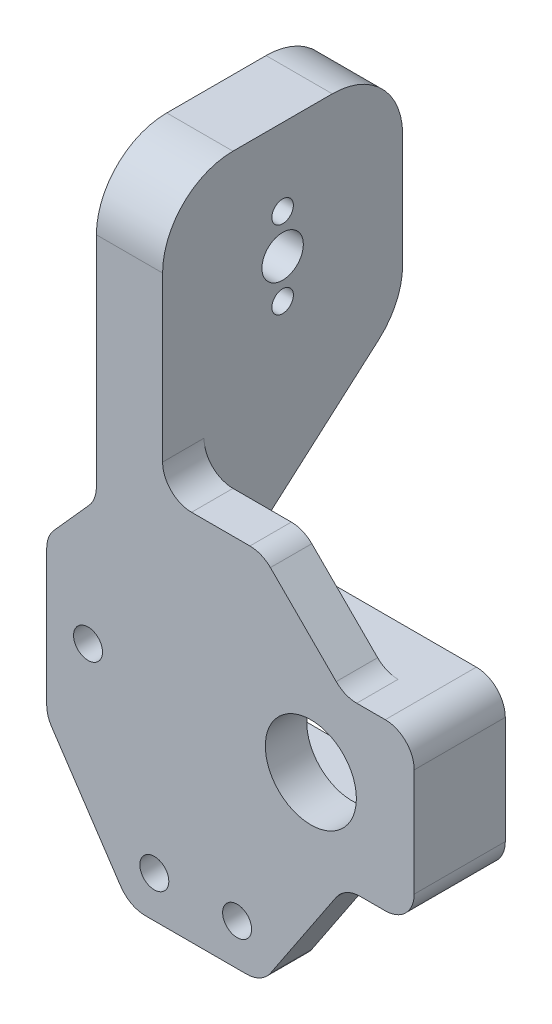
SolidWorks part; units mm, degrees
ref_plane "Front Plane" through (0, 0, 0) normal (0, 0, 1) x (1, 0, 0)
ref_plane "Top Plane" through (0, 0, 0) normal (0, 1, 0) x (1, 0, 0)
ref_plane "Right Plane" through (0, 0, 0) normal (1, 0, 0) x (0, 0, -1)
sketch "Sketch2" plane through (0, 0, 0) normal (0, 0, 1) x (1, 0, 0)
  line L0 (6, -0.2185) -> (14, -0.2185)
  line L1 (14, -0.2185) -> (14, -28)
  line L2 (6, -0.2185) -> (6, -34.9443)
  line L3 (4.9814, -37.6109) -> (1.0186, -42.0415)
  line L4 (0, -44.7082) -> (0, -60.7889)
  line L5 (0.6718, -63.0077) -> (8.8145, -75.2217)
  line L7 (12.1407, -77) -> (23.8593, -77)
  line L8 (34.8125, -63.7812) -> (27.1875, -75.2188)
  line L9 (38.1407, -62) -> (40.4, -62)
  line L10 (44.4, -46) -> (44.4, -58)
  line L11 (37.6569, -42) -> (40.4, -42)
  line L12 (34.8284, -40.8284) -> (27.1716, -33.1716)
  line L13 (18, -32) -> (24.3431, -32)
  line L14 (6, -34.9443) -> (6, -35.1352)
  line L15 (4.9814, -37.6109) -> (5.1087, -37.4685)
  line L16 (0, -60.7889) -> (0, -60.9403)
  line L17 (0.6718, -63.0077) -> (0.5878, -62.8817)
  line L18 (8.8145, -75.2217) -> (9.0744, -75.5748)
  line L19 (12.1407, -77) -> (11.8931, -77)
  line L20 (27.1875, -75.2188) -> (27.0391, -75.4414)
  line L21 (23.8593, -77) -> (24.1269, -77)
  line L22 (34.8125, -63.7812) -> (34.9609, -63.5586)
  line L23 (38.1407, -62) -> (37.8731, -62)
  line L24 (44.4, -58) -> (44.4, -58.5)
  line L25 (40.4, -62) -> (40.9, -62)
  line L26 (40.4, -42) -> (40.9, -42)
  line L27 (44.4, -46) -> (44.4, -45.5)
  line L28 (37.6569, -42) -> (37.4497, -42)
  line L29 (34.8284, -40.8284) -> (34.9749, -40.9749)
  line L30 (14, -28) -> (14, -28.5)
  line L31 (18, -32) -> (17.5, -32)
  line L32 (24.3431, -32) -> (24.5503, -32)
  line L33 (27.1716, -33.1716) -> (27.0251, -33.0251)
  line L34 (1.0186, -42.0415) -> (0.8913, -42.1839)
  line L35 (0, -44.7082) -> (0, -44.5172)
  arc A0 (5.1087, -37.4685) -> (6, -35.1352) centre (2.5, -35.1352) ccw
  arc A1 (0.5878, -62.8817) -> (0, -60.9403) centre (3.5, -60.9403) cw
  arc A2 (11.8931, -77) -> (9.0744, -75.5748) centre (11.8931, -73.5) cw
  arc A3 (24.1269, -77) -> (27.0391, -75.4414) centre (24.1269, -73.5) ccw
  arc A4 (34.9609, -63.5586) -> (37.8731, -62) centre (37.8731, -65.5) cw
  arc A5 (40.9, -62) -> (44.4, -58.5) centre (40.9, -58.5) ccw
  arc A6 (44.4, -45.5) -> (40.9, -42) centre (40.9, -45.5) ccw
  arc A7 (37.4497, -42) -> (34.9749, -40.9749) centre (37.4497, -38.5) cw
  arc A8 (17.5, -32) -> (14, -28.5) centre (17.5, -28.5) cw
  circle A9 centre (31.9101, -52.0014) radius 5.5
  circle A10 centre (23, -72) radius 1.75
  circle A11 centre (13, -72) radius 1.75
  circle A12 centre (4.9951, -52.0029) radius 1.749
  arc A13 (0, -44.5172) -> (0.8913, -42.1839) centre (3.5, -44.5172) cw
  arc A14 (27.0251, -33.0251) -> (24.5503, -32) centre (24.5503, -35.5) ccw
  point P2 (39.2703, -62)
  dimension "D1" = 3.5
  dimension "D3" = 3.5
  dimension "D4" = 3.5
  dimension "D7" = 3.5
  dimension "D8" = 3.5
  dimension "D9" = 3.5
  dimension "D10" = 3.5
  dimension "D11" = 3.5
  dimension "D12" = 3.5
  dimension "D13" = 3.5
  dimension "D25" = 11
  dimension "D26" = 26.915
  dimension "D2" = 180
  dimension "D5" = 14.6794
  dimension "D6" = 3.5553
  dimension "D14" = 76.7815
  dimension "D15" = 44.4
  dimension "D16" = 8
  dimension "D17" = 11.7186
  dimension "D18" = 6
  dimension "D19" = 31.7815
  dimension "D20" = 35
  dimension "D21" = 20
  dimension "D22" = 10.8283
  dimension "D23" = 13.7462
  dimension "D24" = 5.9443
extrude "Boss-Extrude1" add sketch "Sketch2" along normal blind 5
sketch "Sketch3" plane through (0, 0, 0) normal (0, 0, -1) x (-1, 0, 0)
  line L0 (-40.9, -42) -> (-37.4497, -42) construction
  line L1 (-44.4, -58.5) -> (-44.4, -45.5) construction
  line L2 (-37.8731, -62) -> (-40.9, -62) construction
  line L3 (-37.8731, -62) -> (-40.9, -62)
  line L4 (-44.4, -58.5) -> (-44.4, -45.5)
  line L5 (-40.9, -42) -> (-37.4497, -42)
  line L6 (-37.4497, -42) -> (-17.5, -42)
  line L7 (-9.4, -44) -> (-9.4, -58.5)
  line L8 (-12.9, -62) -> (-37.8731, -62)
  line L9 (-14, -0.2185) -> (-6, -0.2185)
  line L10 (-6, -0.2185) -> (-6, -42)
  line L11 (-6, -42) -> (-7.4, -42)
  line L12 (-14, -0.2185) -> (-14, -38.5)
  line L13 (-38.4, -52) -> (-40.7, -52) construction
  line L14 (-38.4, -46) -> (-15.4, -46)
  line L15 (-38.4, -46) -> (-38.4, -58)
  line L16 (-38.4, -58) -> (-15.4, -58)
  line L17 (-15.4, -46) -> (-15.4, -58)
  line L18 (-26.9, -46) -> (-26.9, -58) construction
  line L19 (-15.4, -52) -> (-13.1, -52) construction
  arc A0 (-40.9, -42) -> (-44.4, -45.5) centre (-40.9, -45.5) ccw construction
  arc A1 (-44.4, -58.5) -> (-40.9, -62) centre (-40.9, -58.5) ccw construction
  arc A2 (-44.4, -58.5) -> (-40.9, -62) centre (-40.9, -58.5) ccw
  arc A3 (-40.9, -42) -> (-44.4, -45.5) centre (-40.9, -45.5) ccw
  arc A4 (-14, -38.5) -> (-17.5, -42) centre (-17.5, -38.5) cw
  arc A5 (-9.4, -58.5) -> (-12.9, -62) centre (-12.9, -58.5) cw
  arc A6 (-7.4, -42) -> (-9.4, -44) centre (-7.4, -44) ccw
  circle A7 centre (-40.7, -52) radius 1
  circle A8 centre (-13.1, -52) radius 1
  point P27 (-9.4, -42)
  dimension "D7" = 3.5
  dimension "D8" = 2
  dimension "D9" = 2
  dimension "D1" = 35
  dimension "D2" = 4
  dimension "D3" = 4
  dimension "D4" = 6
  dimension "D5" = 6
  dimension "D6" = 20
  dimension "D10" = 27.6
extrude "Boss-Extrude2" add sketch "Sketch3" along normal blind 6
sketch "Sketch4" plane through (0, 0, -6) normal (0, 0, -1) x (-1, 0, 0)
  line L0 (-14, -0.2185) -> (-6, -0.2185)
  line L1 (-6, -0.2185) -> (-6, -26.2185)
  line L2 (-6, -42) -> (-6, -0.2185) construction
  line L3 (-6, -26.2185) -> (-14, -26.2185)
  line L4 (-14, -0.2185) -> (-14, -38.5) construction
  line L5 (-14, -26.2185) -> (-14, -0.2185)
  dimension "D1" = 26
extrude "Boss-Extrude3" add sketch "Sketch4" along normal blind 18
ref_plane "Plane1" through (10, 0, 0) normal (-1, 0, 0) x (0, 0, 1)
sketch "Sketch5" plane through (10, 0, 0) normal (-1, 0, 0) x (0, 0, 1)
  line L0 (-24, -26.2185) -> (-6, -42)
  line L9 (5, -0.2185) -> (-24, -0.2185)
  line L10 (-24, -0.2185) -> (-24, -26.2185)
  line L11 (-24, -26.2185) -> (-6, -26.2185)
  line L12 (-6, -26.2185) -> (-6, -42)
  line L13 (-6, -42) -> (0, -42)
  line L14 (0, -42) -> (0, -35.1352)
  line L15 (0, -35.1352) -> (5, -35.1352)
  line L16 (5, -35.1352) -> (5, -0.2185)
  line L19 (-24, -26.2185) -> (-6, -26.2185)
  line L20 (-6, -26.2185) -> (-6, -42)
  dimension "D1" = 0
extrude "Boss-Extrude4" add sketch "Sketch5" along normal mid plane 8
fillet "Fillet1" radius 8.5 3 edges at (10, -0.2185, 5) (10, -26.2185, -24) (10, -0.2185, -24)
sketch "Sketch6" plane through (14, 0, 0) normal (1, 0, 0) x (0, 0, -1)
  line L0 (-5, -8.7185) -> (-5, -28.5) construction
  line L1 (3.5, -0.2185) -> (15.5, -0.2185) construction
  line L2 (3.5, -14.2185) -> (15.5, -14.2185) construction
  line L3 (24, -8.7185) -> (24, -22.3666) construction
  line L4 (9.5, -8.7185) -> (9.5, -28.5) construction
  arc A0 (3.5, -0.2185) -> (-5, -8.7185) centre (3.5, -8.7185) ccw construction
  circle A1 centre (9.5, -14.2185) radius 2.5
  circle A2 centre (9.5, -9.5185) radius 1.3
  circle A3 centre (9.5, -18.9185) radius 1.3
  dimension "D6" = 5
  dimension "D7" = 2.6
  dimension "D1" = 29
  dimension "D3" = 14.5
  dimension "D4" = 2
  dimension "D5" = 14
  dimension "D8" = 4.7
  dimension "D2" = 2
extrude "Cut-Extrude1" cut sketch "Sketch6" against normal through all
ref_point "Point1"
ref_point "Point2"
ref_point "Point3"
ref_point "Point4"
ref_point "Point5"
